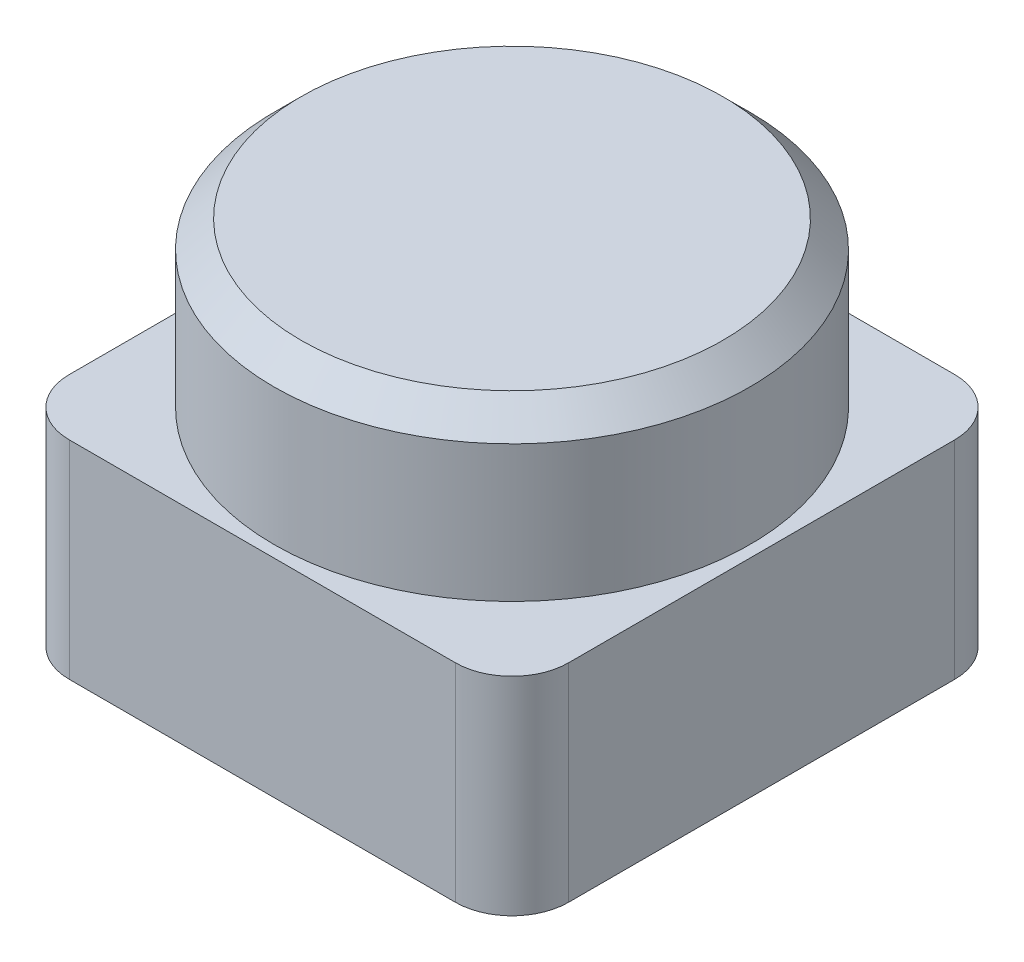
SolidWorks part; units mm, degrees
ref_plane "Front Plane" through (0, 0, 0) normal (0, 0, 1) x (1, 0, 0)
ref_plane "Top Plane" through (0, 0, 0) normal (0, 1, 0) x (1, 0, 0)
ref_plane "Right Plane" through (0, 0, 0) normal (1, 0, 0) x (0, 0, -1)
sketch "Sketch1" plane through (0, 0, 0) normal (0, 1, 0) x (1, 0, 0)
  line L1 (0, 0) -> (55.6, 0)
  line L2 (0, 0) -> (0, 55.6)
  line L3 (0, 55.6) -> (55.6, 55.6)
  line L4 (55.6, 0) -> (55.6, 55.6)
  dimension "D1" = 55.6
  dimension "D2" = 55.6
extrude "Boss-Extrude1" add sketch "Sketch1" along normal blind 23.1
fillet "Fillet1" radius 6.3 4 edges at (55.6, 11.55, -55.6) (0, 11.55, -55.6) (0, 11.55, 0) (55.6, 11.55, 0)
sketch "Sketch2" plane through (0, 0, 0) normal (0, -1, 0) x (1, 0, 0)
  circle A0 centre (6.3, -6.3) radius 1.25
  circle A1 centre (49.3, -6.3) radius 1.25
  circle A2 centre (49.3, -49.3) radius 1.25
  circle A3 centre (6.3, -49.3) radius 1.25
  dimension "D1" = 2.5
extrude "Screw Holes" cut sketch "Sketch2" against normal blind 4
sketch "Sketch3" plane through (0, 23.1, 0) normal (0, 1, 0) x (1, 0, 0)
  line L0 (49.3, 55.6) -> (6.3, 55.6) construction
  line L1 (27.8, 55.6) -> (27.8, 0) construction
  line L2 (6.3, 0) -> (49.3, 0) construction
  line L3 (0, 27.8) -> (55.6, 27.8) construction
  line L4 (0, 49.3) -> (0, 6.3) construction
  line L5 (55.6, 6.3) -> (55.6, 49.3) construction
  circle A0 centre (27.8, 27.8) radius 26.5
  dimension "D1" = 53
extrude "Boss-Extrude2" add sketch "Sketch3" along normal blind 18.2
chamfer "Chamfer1" distance 3 angle 45 1 edges at (27.8, 41.3, -1.3)
